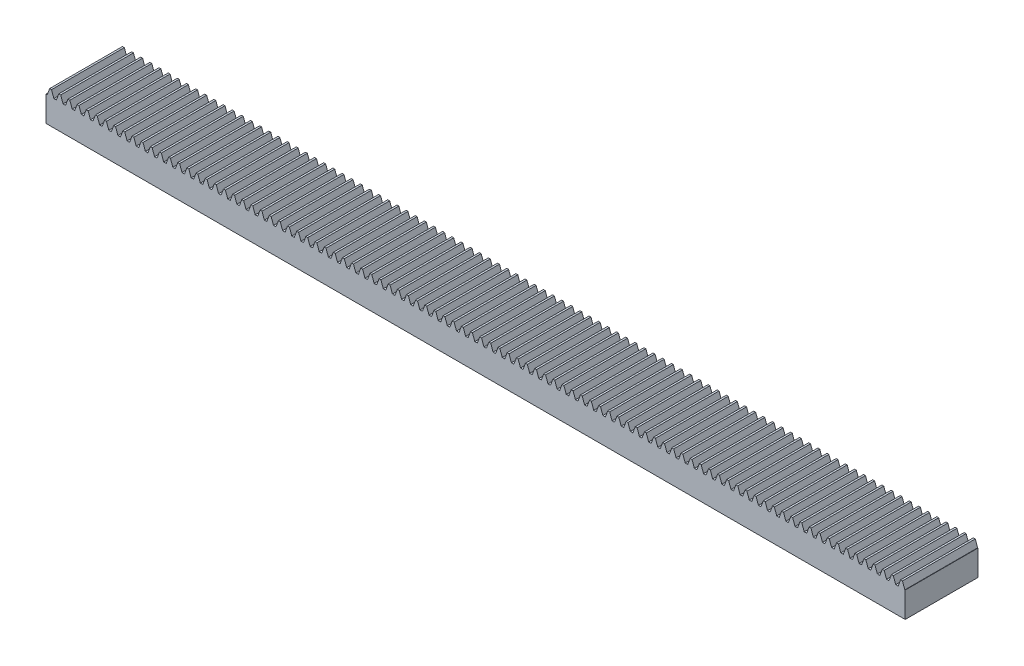
SolidWorks part; units mm, degrees
extrude "Blank" add sketch "BlankSke" against normal blind 50
sketch "BlankSke" plane through (0, 0, 0) normal (0, 0, 1) x (1, 0, 0)
  line L1 (0, 0) -> (590, 0)
  line L2 (0, 0) -> (0, 22)
  line L3 (0, 22) -> (590, 22)
  line L4 (590, 0) -> (590, 22)
  dimension "Length" = 590
  dimension "Blank_height" = 22
ref_plane "Plane1" through (0, 0, 0) normal (0, 0, 1) x (1, 0, 0)
ref_plane "Plane2" through (0, 0, 0) normal (0, 1, 0) x (1, 0, 0)
ref_plane "Plane3" through (0, 0, 0) normal (1, 0, 0) x (0, 0, -1)
other "Configuration Table"
sketch "HoldingSke" plane through (0, 0, 0) normal (0, 1, 0) x (1, 0, 0)
  line L0 (0, 0) -> (0.0696, 0.4951)
  line L1 (-15, 0) -> (100, 0) construction
  line L2 (0, 0) -> (-2.1039, 2.3779)
  line L3 (0, 0) -> (-11.863, 4.5341)
  line L4 (0, 0) -> (-0.7527, 8.6031)
  line L5 (0, 0) -> (-23.7986, -8.8762)
  line L6 (0, 0) -> (-10.5278, -7.1032)
  line L9 (-71.009, 38.7566) -> (483.4097, 240.5485)
  line L10 (-76.2, 4.3779) -> (-56.2, 4.3779)
  line L11 (0, 0) -> (-50, 0)
  line L12 (-76.2, 101.6) -> (-76.133, 101.6)
  line L13 (24.9733, 27.94) -> (52.9518, 28.4284)
  line L14 (24.9733, 27.94) -> (24.9743, 27.94)
  line L15 (24.9733, 27.94) -> (100.4006, 29.5858)
  circle A0 centre (0, 0) radius 19.05
  circle A1 centre (0, 0) radius 10
  circle A2 centre (0, 0) radius 12.7
  dimension "MPH" = 20
  dimension "Diameter" = 38.1
  dimension "Num_teeth" = 95
  dimension "Pitch" = 0.5
  dimension "Show_teeth" = 998
  dimension "Thickness" = 12.7
  dimension "Ap" = 20
  dimension "Pitch_height" = 20
  dimension "Width" = 50
  dimension "Backlash" = 0.067
  dimension "Addendum_fac" = 1
  dimension "Dedendum_fac" = 1.25
  dimension "Clearance_fac" = 0.25
  dimension "Dedendum_add" = 0.001
  dimension "Length" = 590
  dimension "Module" = 2
sketch "TooCutSkeIll" plane through (0, 0, 0) normal (0, 0, 1) x (1, 0, 0)
  line L0 (-2.4806, 21.9474) -> (-0.9819, 17.8296)
  line L1 (-0.5111, 17.5) -> (0.5111, 17.5)
  line L2 (0.9819, 17.8296) -> (2.4806, 21.9474)
  line L3 (590, 22) -> (0, 22) construction
  line L4 (0, 0) -> (0, 64.897) construction
  line L5 (-13.208, 20) -> (12.954, 20) construction
  line L6 (0, 0) -> (590, 0) construction
  line L7 (1.7718, 20) -> (1.7718, 48.7463) construction
  line L8 (-1.7718, 20) -> (-1.7718, 48.7463) construction
  line L9 (2.5558, 22) -> (2.5558, 22.0254)
  line L10 (-2.5558, 22) -> (-2.5558, 22.0254)
  line L11 (-2.5558, 22.0254) -> (2.5558, 22.0254)
  arc A0 (0.5111, 17.5) -> (0.9819, 17.8296) centre (0.5111, 18.001) ccw
  arc A1 (-0.9819, 17.8296) -> (-0.5111, 17.5) centre (-0.5111, 18.001) ccw
  arc A2 (2.5558, 22) -> (2.4806, 21.9474) centre (2.5558, 21.92) ccw
  arc A3 (-2.4806, 21.9474) -> (-2.5558, 22) centre (-2.5558, 21.92) ccw
  dimension "Pitch_height" = 20
  dimension "Addendum_plus" = 2.0254
  dimension "Pressure_angle" = 20
  dimension "Gap_width" = 3.5436
  dimension "Dedendum" = 2.5
extrude "ToothCutIll" [suppressed] cut sketch "TooCutSkeIll" against normal through all
sketch "TooCutSkeSim" plane through (0, 0, 0) normal (0, 0, 1) x (1, 0, 0)
  line L0 (0.8619, 17.5) -> (-0.8619, 17.5)
  line L1 (2.509, 22.0254) -> (0.8619, 17.5)
  line L2 (0, 17.4625) -> (0, 53.467) construction
  line L3 (2.509, 22.0254) -> (-2.509, 22.0254)
  line L6 (-2.509, 22.0254) -> (-0.8619, 17.5)
  line L9 (-1.7718, 20) -> (1.7718, 20) construction
  line L10 (0, 0) -> (590, 0) construction
  line L11 (1.7718, 20) -> (1.7718, 53.467) construction
  line L12 (-1.7718, 20) -> (-1.7718, 53.467) construction
  dimension "Pitch_height" = 20
  dimension "Addendum_plus" = 2.0254
  dimension "Pressure_angle" = 20
  dimension "Gap_width" = 3.5436
  dimension "Dedendum" = 2.5
extrude "ToothCutSim" cut sketch "TooCutSkeSim" against normal through all
pattern_linear "TeethCuts" count 95 spacing 6.2832 along (1, 0, 0) of "ToothCutIll", "ToothCutSim"
equation "' \"Module@HoldingSke\" = 6.35"
equation "' \"Num_teeth@HoldingSke\" = 12"
equation "' \"Ap@HoldingSke\" =  20"
equation "' \"Ap@HoldingSke\" = 20"
equation "' \"Width@HoldingSke\" = 0.25 * 25.4"
equation "' \"Show_teeth@HoldingSke\" = 500"
equation "' \"Backlash@HoldingSke\" = 0.009 * 25.4"
equation "' \"Addendum_fac@HoldingSke\" = 1.0"
equation "' \"Dedendum_fac@HoldingSke\" = 1.25"
equation "' \"Dedendum_add@HoldingSke\" = 0.00005 * 25.4"
equation "' \"Clearance_fac@HoldingSke\" = 0.25"
equation "' \"Pitch_height@HoldingSke\" = 1 * 25.4"
equation "' \"Length@HoldingSke\" = 4.71 * 25.4"
equation "\"Pitch@HoldingSke\" = 1 / \"Module@HoldingSke\""
equation "\"MPH@HoldingSke\" = \"Dedendum_fac@HoldingSke\" / \"Pitch@HoldingSke\" + 2 * \"Dedendum_add@HoldingSke\" + 0.002 * 25.4"
equation "\"MPH@HoldingSke\" = ((sgn( \"MPH@HoldingSke\" - \"Pitch_height@HoldingSke\")+1)*( \"MPH@HoldingSke\" - \"Pitch_height@HoldingSke\"))/2 + \"Pitch_height@HoldingSke\""
equation "\"Blank_height@BlankSke\" = \"Pitch_height@HoldingSke\" + \"Addendum_fac@HoldingSke\"  / \"Pitch@HoldingSke\" "
equation "\"Length@BlankSke\" =  \"Length@HoldingSke\""
equation "\"Face_width@Blank\" = \"Width@HoldingSke\""
equation "\"Pressure_angle@TooCutSkeIll\" = \"Ap@HoldingSke\""
equation "\"Addendum_plus@TooCutSkeIll\" =  \"Addendum_fac@HoldingSke\"  / \"Pitch@HoldingSke\" + 0.001 *25.4"
equation "\"Dedendum@TooCutSkeIll\" = \"Dedendum_fac@HoldingSke\"  / \"Pitch@HoldingSke\""
equation "\"Pitch_height@TooCutSkeIll\" =  \"MPH@HoldingSke\""
equation "\"Gap_width@TooCutSkeIll\" = 3.14159265 / 2 / \"Pitch@HoldingSke\" + 6 * \"Backlash@HoldingSke\""
equation "\"Pressure_angle@TooCutSkeSim\" = \"Ap@HoldingSke\""
equation "\"Addendum_plus@TooCutSkeSim\" =  \"Addendum_fac@HoldingSke\"  / \"Pitch@HoldingSke\" + 0.001 * 25.4"
equation "\"Dedendum@TooCutSkeSim\" = \"Dedendum_fac@HoldingSke\"  / \"Pitch@HoldingSke\""
equation "\"Pitch_height@TooCutSkeSim\" =  \"MPH@HoldingSke\""
equation "\"Gap_width@TooCutSkeSim\" = 3.14159265 / 2 / \"Pitch@HoldingSke\" + 6 * \"Backlash@HoldingSke\""
equation "\"Root_fillet@TooCutSkeIll\" = \"Clearance_fac@HoldingSke\" / \"Pitch@HoldingSke\" + \"Dedendum_add@HoldingSke\""
equation "\"Break_rad@TooCutSkeIll\" = 0.02 / \"Pitch@HoldingSke\" * 2"
equation "\"Linear_pitch@TeethCuts\" = 3.14159265 / \"Pitch@HoldingSke\""
equation "\"Num_teeth@HoldingSke\" = int( ( \"Length@HoldingSke\" + 0 ) / (3.14159265 / \"Pitch@HoldingSke\")) + 0.9999  + 1"
equation " \"Num_teeth@TeethCuts\" = int( \"Show_teeth@HoldingSke\" ) + 1"
equation " \"Num_teeth@TeethCuts\" = ((sgn( \"Num_teeth@TeethCuts\" - \"Num_teeth@HoldingSke\" )-1)*( \"Num_teeth@TeethCuts\" - \"Num_teeth@HoldingSke\" ))/-2+ \"Num_teeth@HoldingSke\""
equation " \"Num_teeth@TeethCuts\" = ((sgn( \"Num_teeth@TeethCuts\" - 2.0)+1)*( \"Num_teeth@TeethCuts\" - 2.0))/2 +2.0"
